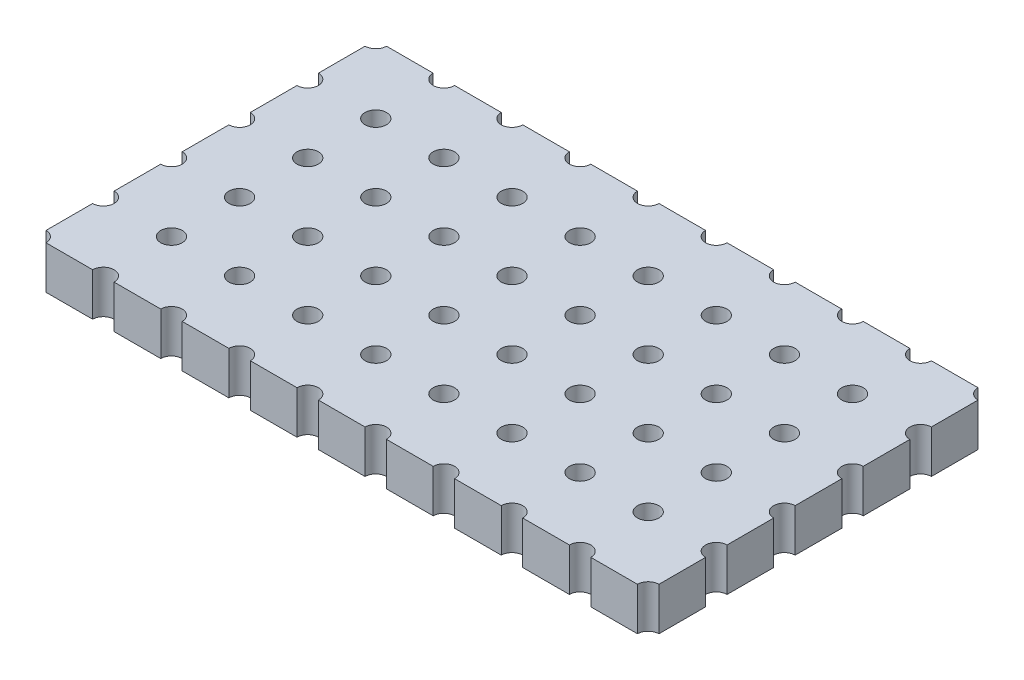
SolidWorks part; units mm, degrees
ref_plane "Front Plane" through (0, 0, 0) normal (0, 0, 1) x (1, 0, 0)
ref_plane "Top Plane" through (0, 0, 0) normal (0, 1, 0) x (1, 0, 0)
ref_plane "Right Plane" through (0, 0, 0) normal (1, 0, 0) x (0, 0, -1)
sketch "Sketch2" plane through (0, 0, 0) normal (0, 1, 0) x (1, 0, 0)
  line L1 (-11.43, -6.35) -> (11.43, -6.35)
  line L2 (-11.43, -6.35) -> (-11.43, 6.35)
  line L3 (-11.43, 6.35) -> (11.43, 6.35)
  line L4 (11.43, -6.35) -> (11.43, 6.35)
  line L5 (-11.43, -6.35) -> (11.43, 6.35) construction
  line L6 (-11.43, 6.35) -> (11.43, -6.35) construction
  point P0 (0, 0)
  dimension "D1" = 22.86
  dimension "D2" = 12.7
extrude "Boss-Extrude1" add sketch "Sketch2" along normal mid plane 1.6
sketch "Sketch3" plane through (0, 0.8, 0) normal (0, 1, 0) x (1, 0, 0)
  circle A0 centre (-11.43, 6.35) radius 0.4
  dimension "D1" = 0.8
extrude "Cut-Extrude1" cut sketch "Sketch3" against normal through all
pattern_linear "LPattern1" count 10 spacing 2.54 along (1, 0, 0) count 6 spacing 2.54 along (0, 0, 1) of "Cut-Extrude1"
